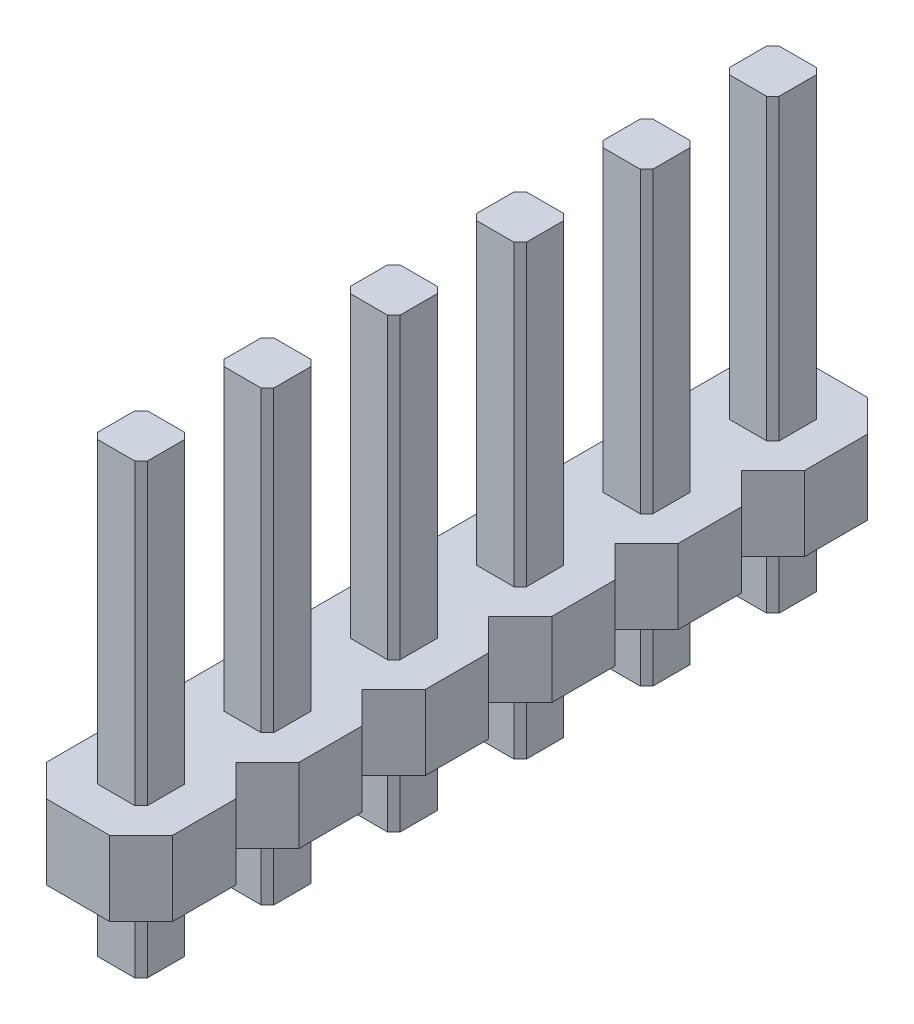
SolidWorks part; units mm, degrees
ref_plane "Plan de face" through (0, 0, 0) normal (0, 0, 1) x (1, 0, 0)
ref_plane "Plan de dessus" through (0, 0, 0) normal (0, 1, 0) x (1, 0, 0)
ref_plane "Plan de droite" through (0, 0, 0) normal (1, 0, 0) x (0, 0, -1)
sketch "Sketch1" plane through (0, 0, 0) normal (0, 1, 0) x (1, 0, 0)
  line L0 (-0.635, 10.16) -> (0.635, 10.16)
  line L1 (0.635, 10.16) -> (1.27, 9.525)
  line L2 (1.27, 9.525) -> (1.27, 8.255)
  line L3 (1.27, 8.255) -> (0.635, 7.62)
  line L4 (-0.635, 10.16) -> (-1.27, 9.525)
  line L5 (-1.27, 9.525) -> (-1.27, 8.255)
  line L6 (-1.27, 8.255) -> (-0.635, 7.62)
  line L7 (0.635, 7.62) -> (1.27, 6.985)
  line L8 (1.27, 6.985) -> (1.27, 5.715)
  line L9 (1.27, 5.715) -> (0.635, 5.08)
  line L10 (-0.635, 7.62) -> (-1.27, 6.985)
  line L11 (-1.27, 6.985) -> (-1.27, 5.715)
  line L12 (-1.27, 5.715) -> (-0.635, 5.08)
  line L13 (0.635, 5.08) -> (1.27, 4.445)
  line L14 (1.27, 4.445) -> (1.27, 3.175)
  line L15 (1.27, 3.175) -> (0.635, 2.54)
  line L16 (-0.635, 5.08) -> (-1.27, 4.445)
  line L17 (-1.27, 4.445) -> (-1.27, 3.175)
  line L18 (-1.27, 3.175) -> (-0.635, 2.54)
  line L19 (0.635, 2.54) -> (1.27, 1.905)
  line L20 (1.27, 1.905) -> (1.27, 0.635)
  line L21 (1.27, 0.635) -> (0.635, 0)
  line L22 (-0.635, 2.54) -> (-1.27, 1.905)
  line L23 (-1.27, 1.905) -> (-1.27, 0.635)
  line L24 (-1.27, 0.635) -> (-0.635, 0)
  line L25 (0.635, 0) -> (1.27, -0.635)
  line L26 (1.27, -0.635) -> (1.27, -1.905)
  line L27 (1.27, -1.905) -> (0.635, -2.54)
  line L28 (-0.635, 0) -> (-1.27, -0.635)
  line L29 (-1.27, -0.635) -> (-1.27, -1.905)
  line L30 (-1.27, -1.905) -> (-0.635, -2.54)
  line L31 (0.635, -2.54) -> (1.27, -3.175)
  line L32 (1.27, -3.175) -> (1.27, -4.445)
  line L33 (1.27, -4.445) -> (0.635, -5.08)
  line L34 (-0.635, -2.54) -> (-1.27, -3.175)
  line L35 (-1.27, -3.175) -> (-1.27, -4.445)
  line L36 (-1.27, -4.445) -> (-0.635, -5.08)
  line L50 (-0.635, 7.62) -> (0.635, 7.62) construction
  line L51 (0, 10.16) -> (0, 7.62) construction
  line L52 (-0.635, -5.08) -> (0.635, -5.08)
  point P0 (0, 8.89)
  point P1 (0, 8.89)
  point P54 (0, 8.89)
extrude "Boss-Extrude1" add sketch "Sketch1" along normal blind 1.5
sketch "Sketch3" plane through (0, 1.5, 0) normal (0, 1, 0) x (1, 0, 0)
  line L0 (-1.27, 8.89) -> (1.27, 8.89) construction
  line L1 (-1.27, 9.525) -> (-1.27, 8.255) construction
  line L2 (1.27, 8.255) -> (1.27, 9.525) construction
  line L3 (0.375, 9.39) -> (0.5, 9.265)
  line L4 (-0.375, 9.39) -> (0.375, 9.39)
  line L5 (-0.5, 9.265) -> (-0.5, 8.515)
  line L6 (-0.375, 8.39) -> (0.375, 8.39)
  line L7 (0.5, 9.265) -> (0.5, 8.515)
  line L8 (-0.5, 9.39) -> (0.5, 8.39) construction
  line L9 (-0.5, 8.39) -> (0.5, 9.39) construction
  line L10 (0.375, 8.39) -> (0.5, 8.515)
  line L11 (-0.5, 8.515) -> (-0.375, 8.39)
  line L12 (-0.5, 9.265) -> (-0.375, 9.39)
  line L13 (0.375, 6.85) -> (0.5, 6.725)
  line L14 (-0.375, 6.85) -> (0.375, 6.85)
  line L15 (-0.5, 6.725) -> (-0.5, 5.975)
  line L16 (-0.375, 5.85) -> (0.375, 5.85)
  line L17 (0.5, 6.725) -> (0.5, 5.975)
  line L18 (0.375, 5.85) -> (0.5, 5.975)
  line L19 (-0.5, 5.975) -> (-0.375, 5.85)
  line L20 (-0.5, 6.725) -> (-0.375, 6.85)
  line L21 (-1.27, 6.35) -> (1.27, 6.35) construction
  line L22 (-0.5, 6.85) -> (0.5, 5.85) construction
  line L23 (-0.5, 5.85) -> (0.5, 6.85) construction
  line L24 (0.375, 4.31) -> (0.5, 4.185)
  line L25 (-0.375, 4.31) -> (0.375, 4.31)
  line L26 (-0.5, 4.185) -> (-0.5, 3.435)
  line L27 (-0.375, 3.31) -> (0.375, 3.31)
  line L28 (0.5, 4.185) -> (0.5, 3.435)
  line L29 (0.375, 3.31) -> (0.5, 3.435)
  line L30 (-0.5, 3.435) -> (-0.375, 3.31)
  line L31 (-0.5, 4.185) -> (-0.375, 4.31)
  line L32 (-1.27, 3.81) -> (1.27, 3.81) construction
  line L33 (-0.5, 4.31) -> (0.5, 3.31) construction
  line L34 (-0.5, 3.31) -> (0.5, 4.31) construction
  line L35 (0.375, 1.77) -> (0.5, 1.645)
  line L36 (-0.375, 1.77) -> (0.375, 1.77)
  line L37 (-0.5, 1.645) -> (-0.5, 0.895)
  line L38 (-0.375, 0.77) -> (0.375, 0.77)
  line L39 (0.5, 1.645) -> (0.5, 0.895)
  line L40 (0.375, 0.77) -> (0.5, 0.895)
  line L41 (-0.5, 0.895) -> (-0.375, 0.77)
  line L42 (-0.5, 1.645) -> (-0.375, 1.77)
  line L43 (-1.27, 1.27) -> (1.27, 1.27) construction
  line L44 (-0.5, 1.77) -> (0.5, 0.77) construction
  line L45 (-0.5, 0.77) -> (0.5, 1.77) construction
  line L46 (0.375, -0.77) -> (0.5, -0.895)
  line L47 (-0.375, -0.77) -> (0.375, -0.77)
  line L48 (-0.5, -0.895) -> (-0.5, -1.645)
  line L49 (-0.375, -1.77) -> (0.375, -1.77)
  line L50 (0.5, -0.895) -> (0.5, -1.645)
  line L51 (0.375, -1.77) -> (0.5, -1.645)
  line L52 (-0.5, -1.645) -> (-0.375, -1.77)
  line L53 (-0.5, -0.895) -> (-0.375, -0.77)
  line L54 (-1.27, -1.27) -> (1.27, -1.27) construction
  line L55 (-0.5, -0.77) -> (0.5, -1.77) construction
  line L56 (-0.5, -1.77) -> (0.5, -0.77) construction
  line L57 (0.375, -3.31) -> (0.5, -3.435)
  line L58 (-0.375, -3.31) -> (0.375, -3.31)
  line L59 (-0.5, -3.435) -> (-0.5, -4.185)
  line L60 (-0.375, -4.31) -> (0.375, -4.31)
  line L61 (0.5, -3.435) -> (0.5, -4.185)
  line L62 (0.375, -4.31) -> (0.5, -4.185)
  line L63 (-0.5, -4.185) -> (-0.375, -4.31)
  line L64 (-0.5, -3.435) -> (-0.375, -3.31)
  line L65 (-1.27, -3.81) -> (1.27, -3.81) construction
  line L66 (-0.5, -3.31) -> (0.5, -4.31) construction
  line L67 (-0.5, -4.31) -> (0.5, -3.31) construction
  point P6 (0, 8.89)
  point P22 (0, 6.35)
  point P37 (0, 3.81)
  point P52 (0, 1.27)
  point P67 (0, -1.27)
  point P82 (0, -3.81)
  dimension "D1" = 1
  dimension "D2" = 1
  dimension "D3" = 6
extrude "Boss-Extrude2" add sketch "Sketch3" along normal blind 6 and the other way blind 3
